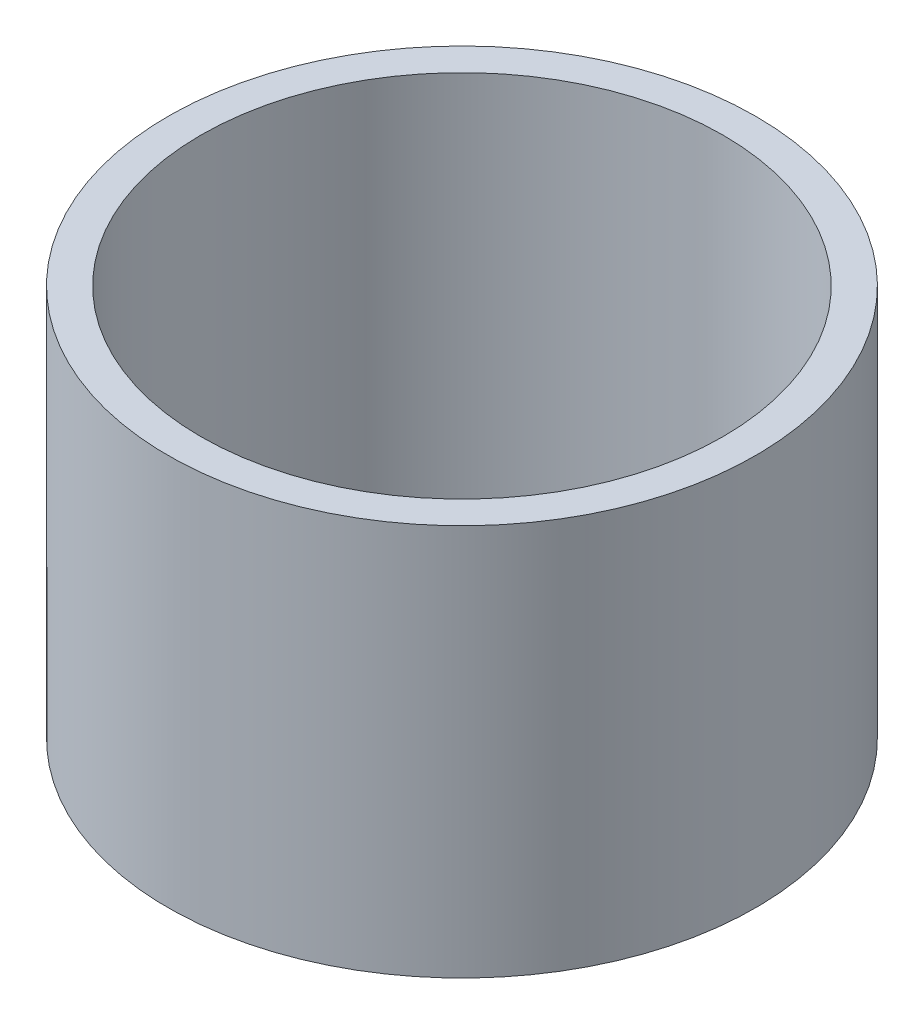
SolidWorks part; units mm, degrees
ref_plane "Front Plane" through (0, 0, 0) normal (0, 0, 1) x (1, 0, 0)
ref_plane "Top Plane" through (0, 0, 0) normal (0, 1, 0) x (1, 0, 0)
ref_plane "Right Plane" through (0, 0, 0) normal (1, 0, 0) x (0, 0, -1)
sketch "Sketch1" plane through (0, 0, 0) normal (0, 1, 0) x (1, 0, 0)
  circle A0 centre (0, 0) radius 12.7
  circle A1 centre (0, 0) radius 14.2875
  dimension "D1" = 25.4
  dimension "D2" = 28.575
extrude "Boss-Extrude1" add sketch "Sketch1" along normal blind 19.05
